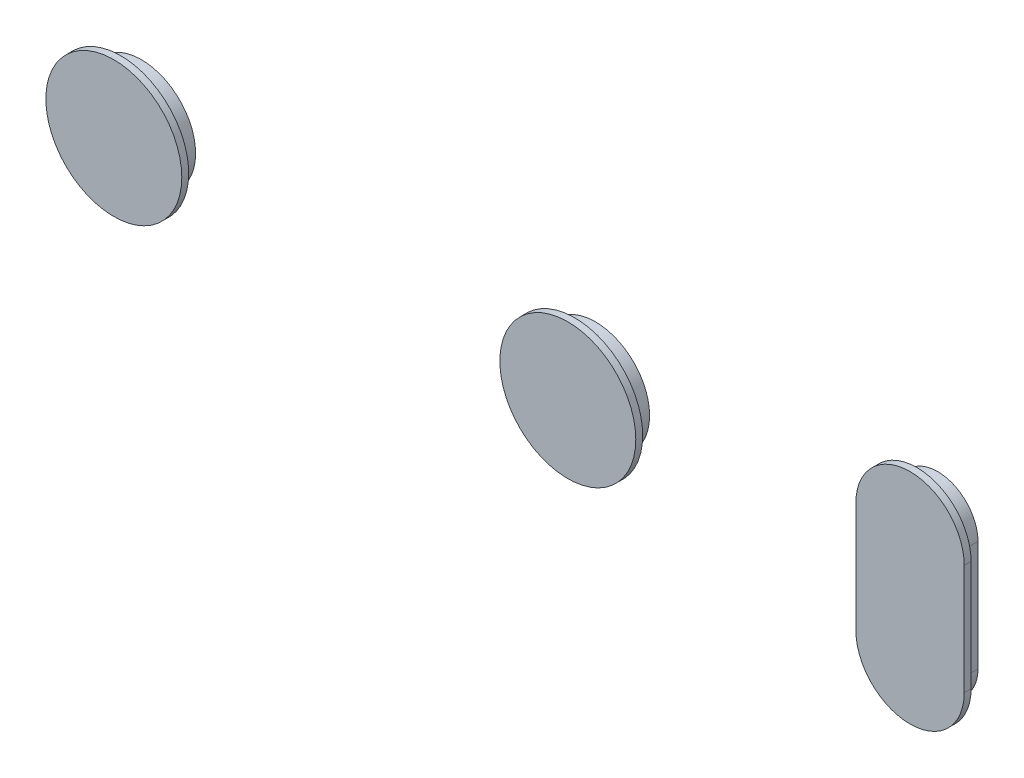
SolidWorks part; units mm, degrees
ref_plane "Front Plane" through (0, 0, 0) normal (0, 0, 1) x (1, 0, 0)
ref_plane "Top Plane" through (0, 0, 0) normal (0, 1, 0) x (1, 0, 0)
ref_plane "Right Plane" through (0, 0, 0) normal (1, 0, 0) x (0, 0, -1)
sketch "Sketch1" plane through (0, 0, 0) normal (0, 0, 1) x (1, 0, 0)
  line L4 (307.8413, 297.7528) -> (307.8413, 281.7528)
  line L5 (319.5413, 281.7528) -> (319.5413, 297.7528)
  line L6 (307.8413, 297.7528) -> (307.8413, 281.7528)
  line L7 (319.5413, 281.7528) -> (319.5413, 297.7528)
  circle A2 centre (198.2913, 289.7528) radius 7.85
  circle A3 centre (198.2913, 289.7528) radius 7.85
  circle A5 centre (264.0913, 289.7528) radius 7.85
  circle A6 centre (264.0913, 289.7528) radius 7.85
  arc A11 (319.5413, 297.7528) -> (307.8413, 297.7528) centre (313.6913, 297.7528) ccw
  arc A12 (307.8413, 281.7528) -> (319.5413, 281.7528) centre (313.6913, 281.7528) ccw
  arc A13 (319.5413, 297.7528) -> (307.8413, 297.7528) centre (313.6913, 297.7528) ccw
  arc A14 (307.8413, 281.7528) -> (319.5413, 281.7528) centre (313.6913, 281.7528) ccw
  dimension "D1" = 0.15
  dimension "D2" = 0.15
  dimension "D3" = 0.15
extrude "Boss-Extrude1" add sketch "Sketch1" against normal up to surface (3 mm away)
sketch "Sketch2" plane through (0, 0, 0) normal (0, 0, 1) x (1, 0, 0)
  line L4 (305.8413, 297.7528) -> (305.8413, 281.7528)
  line L5 (321.5413, 281.7528) -> (321.5413, 297.7528)
  line L6 (305.8413, 297.7528) -> (305.8413, 281.7528)
  line L7 (321.5413, 281.7528) -> (321.5413, 297.7528)
  circle A2 centre (198.2913, 289.7528) radius 9.85
  circle A3 centre (198.2913, 289.7528) radius 9.85
  circle A5 centre (264.0913, 289.7528) radius 9.85
  circle A6 centre (264.0913, 289.7528) radius 9.85
  arc A10 (321.5413, 297.7528) -> (305.8413, 297.7528) centre (313.6913, 297.7528) ccw
  arc A11 (305.8413, 281.7528) -> (321.5413, 281.7528) centre (313.6913, 281.7528) ccw
  arc A12 (321.5413, 297.7528) -> (305.8413, 297.7528) centre (313.6913, 297.7528) ccw
  arc A13 (305.8413, 281.7528) -> (321.5413, 281.7528) centre (313.6913, 281.7528) ccw
  dimension "D1" = 2
  dimension "D2" = 2
  dimension "D3" = 2
extrude "Boss-Extrude2" add sketch "Sketch2" along normal blind 1
